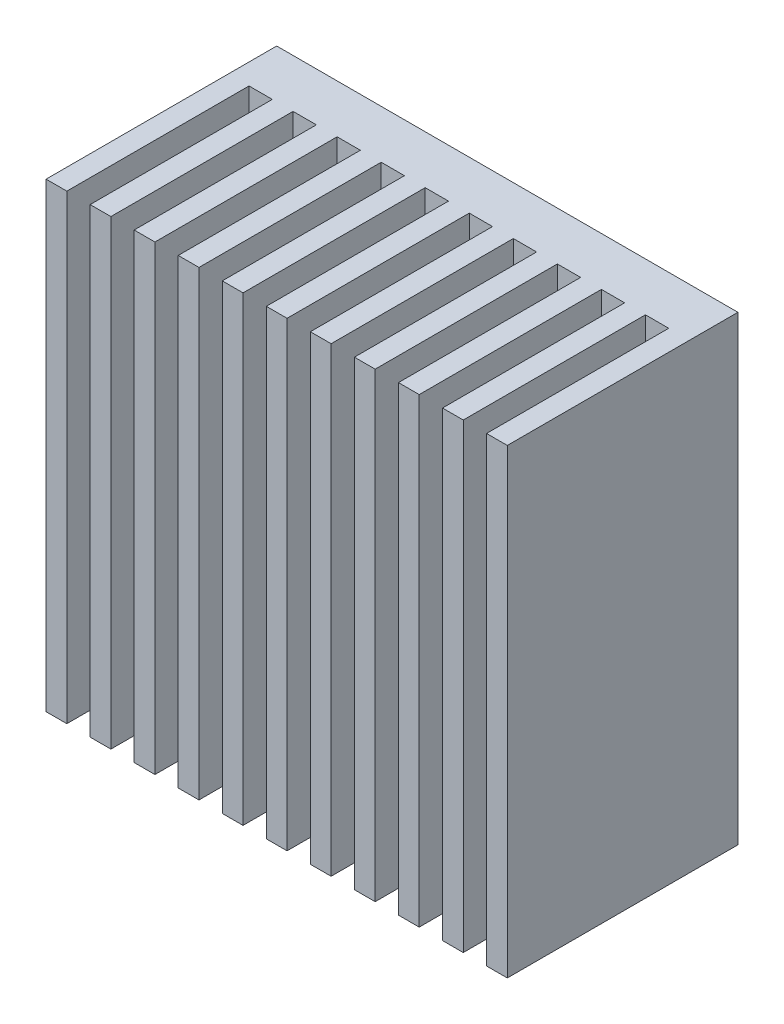
SolidWorks part; units mm, degrees
ref_plane "Plan de face" through (0, 0, 0) normal (0, 0, 1) x (1, 0, 0)
ref_plane "Plan de dessus" through (0, 0, 0) normal (0, 1, 0) x (1, 0, 0)
ref_plane "Plan de droite" through (0, 0, 0) normal (1, 0, 0) x (0, 0, -1)
sketch "Esquisse1" plane through (0, 0, 0) normal (0, 0, 1) x (1, 0, 0)
  line L1 (0, 0) -> (40, 0)
  line L2 (0, 0) -> (0, 40)
  line L3 (0, 40) -> (40, 40)
  line L4 (40, 0) -> (40, 40)
  dimension "D1" = 40
extrude "Boss.-Extru.1" add sketch "Esquisse1" along normal blind 4.2
sketch "Esquisse2" plane through (0, 0, 0) normal (0, -1, 0) x (1, 0, 0)
  line L0 (0, 0) -> (40, 0) construction
  line L1 (0, 4.2) -> (1.8, 4.2)
  line L2 (0, 4.2) -> (0, 20)
  line L3 (0, 20) -> (1.8, 20)
  line L4 (1.8, 4.2) -> (1.8, 20)
  dimension "D1" = 1.8
  dimension "D2" = 20
extrude "Boss.-Extru.2" add sketch "Esquisse2" against normal up to surface (40 mm away) up to face at (20, 40, 2.1)
pattern_linear "Répétition linéaire1" count 11 spacing 3.82 along (1, 0, 0) of "Boss.-Extru.2"
sketch "Esquisse3" plane through (0, 0, 0) normal (0, 0, -1) x (-1, 0, 0)
  line L0 (-40, 20) -> (-30, 20) construction
  line L1 (-40, 0) -> (-40, 40) construction
  line L2 (-30, 20) -> (-10, 20) construction
  line L3 (-10, 20) -> (0, 20) construction
  line L4 (0, 40) -> (0, 0) construction
  circle A0 centre (-30, 20) radius 1.25
  circle A1 centre (-10, 20) radius 1.25
  dimension "D1" = 2.5
  dimension "D2" = 20
extrude "Enlèv. mat.-Extru.1" cut sketch "Esquisse3" against normal blind 10
